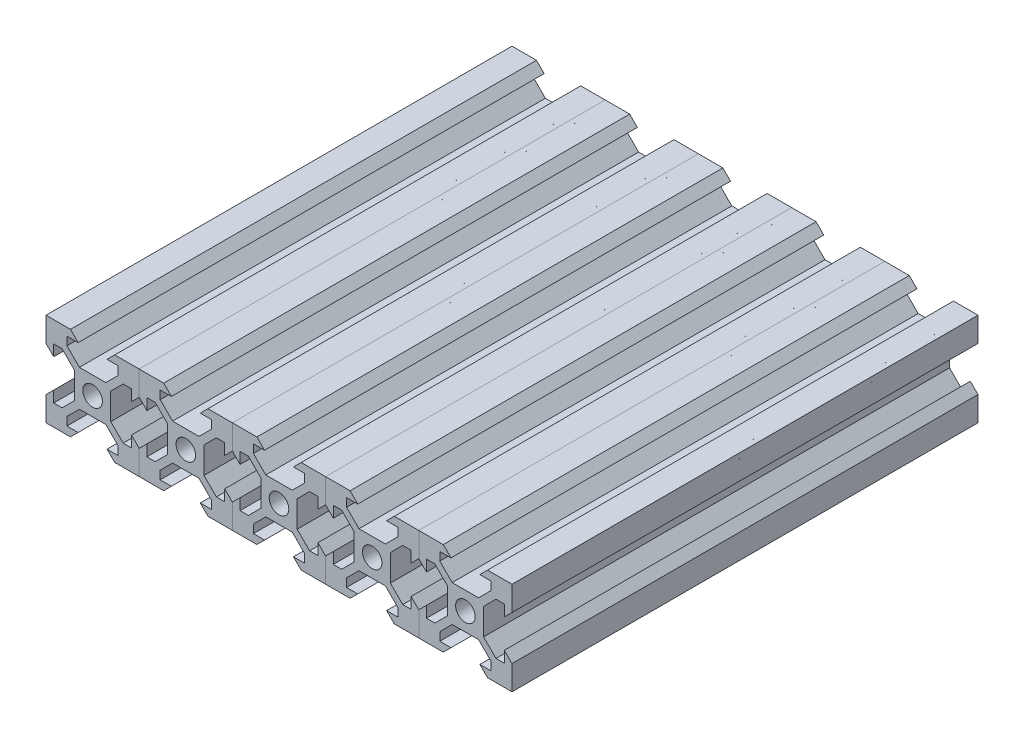
SolidWorks part; units mm, degrees
material "6061-T6 (SS)"
ref_plane "Front Plane" through (0, 0, 0) normal (0, 0, 1) x (1, 0, 0)
ref_plane "Top Plane" through (0, 0, 0) normal (0, 1, 0) x (1, 0, 0)
ref_plane "Right Plane" through (0, 0, 0) normal (1, 0, 0) x (0, 0, -1)
sketch "Sketch1" plane through (0, 0, 0) normal (0, 0, 1) x (1, 0, 0)
  line L0 (2.8343, 3.894) -> (5.5, 6.5588)
  line L1 (2.8343, -3.894) -> (-2.8343, -3.894)
  line L2 (3.8948, -2.8332) -> (3.8948, 2.8332)
  line L3 (2.8343, 3.894) -> (-2.8343, 3.894)
  line L4 (-3.8948, -2.8332) -> (-3.8948, 2.8332)
  line L5 (3.8994, -3.9006) -> (-3.8994, 3.9006) construction
  line L6 (3.9006, 3.8994) -> (-3.9006, -3.8994) construction
  line L7 (10, 4.747) -> (10, 9.9986)
  line L8 (5.5, 6.5588) -> (5.5, 8.3491)
  line L9 (5.5, 8.3491) -> (3.1, 8.3491)
  line L10 (3.1, 8.3491) -> (4.75, 9.9986)
  line L11 (4.75, 9.9986) -> (10, 9.9986)
  line L12 (8.35, 3.0975) -> (10, 4.747)
  line L13 (8.3507, 5.4975) -> (8.35, 3.0975)
  line L14 (6.5605, 5.498) -> (8.3507, 5.4975)
  line L15 (3.8948, 2.8332) -> (6.5605, 5.498)
  line L16 (0, -55) -> (0, 55) construction
  line L17 (-3.8948, 2.8332) -> (-6.5605, 5.498)
  line L18 (-6.5605, 5.498) -> (-8.3507, 5.4975)
  line L19 (-8.3507, 5.4975) -> (-8.35, 3.0975)
  line L20 (-8.35, 3.0975) -> (-10, 4.747)
  line L21 (-4.75, 9.9986) -> (-10, 9.9986)
  line L22 (-3.1, 8.3491) -> (-4.75, 9.9986)
  line L23 (-5.5, 8.3491) -> (-3.1, 8.3491)
  line L24 (-5.5, 6.5588) -> (-5.5, 8.3491)
  line L25 (-10, 4.747) -> (-10, 9.9986)
  line L26 (-2.8343, 3.894) -> (-5.5, 6.5588)
  line L27 (55, 0) -> (-55, 0) construction
  line L28 (3.8948, -2.8332) -> (6.5605, -5.498)
  line L29 (2.8343, -3.894) -> (5.5, -6.5588)
  line L30 (-3.8948, -2.8332) -> (-6.5605, -5.498)
  line L31 (-2.8343, -3.894) -> (-5.5, -6.5588)
  line L32 (-8.3507, -5.4975) -> (-8.35, -3.0975)
  line L33 (-8.35, -3.0975) -> (-10, -4.747)
  line L34 (8.3507, -5.4975) -> (8.35, -3.0975)
  line L35 (8.35, -3.0975) -> (10, -4.747)
  line L36 (-10, -4.747) -> (-10, -9.9986)
  line L37 (-5.5, -6.5588) -> (-5.5, -8.3491)
  line L38 (-5.5, -8.3491) -> (-3.1, -8.3491)
  line L39 (-3.1, -8.3491) -> (-4.75, -9.9986)
  line L40 (-4.75, -9.9986) -> (-10, -9.9986)
  line L41 (-6.5605, -5.498) -> (-8.3507, -5.4975)
  line L42 (6.5605, -5.498) -> (8.3507, -5.4975)
  line L43 (4.75, -9.9986) -> (10, -9.9986)
  line L44 (3.1, -8.3491) -> (4.75, -9.9986)
  line L45 (5.5, -8.3491) -> (3.1, -8.3491)
  line L46 (5.5, -6.5588) -> (5.5, -8.3491)
  line L47 (10, -4.747) -> (10, -9.9986)
  circle A0 centre (0, 0) radius 2.1
  point P0 (0, 0)
  dimension "D6" = 4.2
  dimension "D1" = 7.8
  dimension "D2" = 20
  dimension "D3" = 11
  dimension "D4" = 9.5
  dimension "D5" = 6.2
  dimension "D7" = 1.5
extrude "Boss-Extrude1" add sketch "Sketch1" along normal blind 100
pattern_linear "MatrizL1" count 5 spacing 20 along (1, 0, 0) of bodies 101
